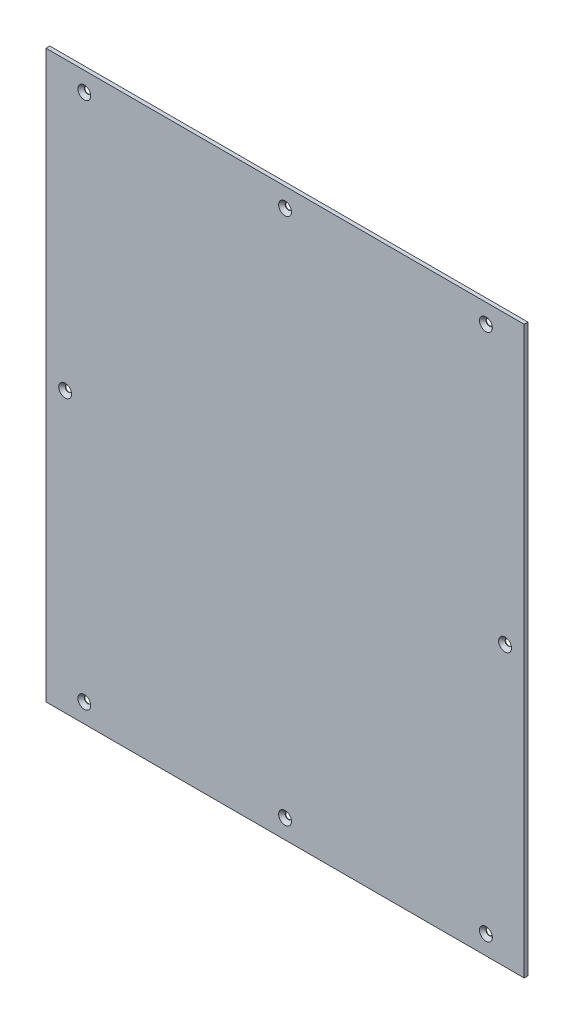
SolidWorks part; units mm, degrees
ref_plane "Front Plane" through (0, 0, 0) normal (0, 0, 1) x (1, 0, 0)
ref_plane "Top Plane" through (0, 0, 0) normal (0, 1, 0) x (1, 0, 0)
ref_plane "Right Plane" through (0, 0, 0) normal (1, 0, 0) x (0, 0, -1)
sketch "Sketch1" plane through (0, 0, 0) normal (0, 0, 1) x (1, 0, 0)
  line L1 (-250, -296) -> (250, -296)
  line L2 (-250, -296) -> (-250, 296)
  line L3 (-250, 296) -> (250, 296)
  line L4 (250, -296) -> (250, 296)
  line L5 (-250, -296) -> (250, 296) construction
  line L6 (-250, 296) -> (250, -296) construction
  point P0 (0, 0)
  dimension "D1" = 500
  dimension "D2" = 592
extrude "Boss-Extrude1" add sketch "Sketch1" along normal blind 4
sketch "Sketch2" plane through (0, 0, 4) normal (0, 0, 1) x (1, 0, 0)
  line L0 (-230, 378.3904) -> (-230, -313.5535) construction
  line L17 (-435.4748, 276) -> (450.358, 276) construction
  line L18 (-427.4037, -276) -> (432.8239, -276) construction
  line L19 (-250, 296) -> (-250, -296) construction
  line L20 (-250, -296) -> (250, -296) construction
  line L21 (250, 296) -> (-250, 296) construction
  line L22 (250, -296) -> (250, 296) construction
  line L23 (230, 365.8937) -> (230, -292.0763) construction
  point P32 (-210, -276)
  point P33 (210, -276)
  point P34 (-210, 276)
  point P35 (210, 276)
  point P36 (-230, -4)
  point P37 (230, -4)
  point P38 (0, 276)
  point P39 (0, -276)
  dimension "D2" = 40
  dimension "D3" = 40
  dimension "D4" = 40
  dimension "D5" = 40
  dimension "D6" = 300
  dimension "D7" = 20
  dimension "D8" = 300
  dimension "D9" = 20
  dimension "D10" = 20
  dimension "D11" = 20
  dimension "D18" = 0
  dimension "D19" = 0
hole_wizard "CSK for M6 Hex Socket Countersunk Cap Screw1" positions "Sketch3" profile "Sketch4" countersink size "M6" standard "ISO" end condition through all
sketch "Sketch3" plane through (0, 0, 4) normal (0, 0, 1) x (1, 0, 0)
  point P0 (-230, -4)
  point P3 (230, -4)
  point P6 (-210, -276)
  point P9 (0, -276)
  point P12 (210, -276)
  point P15 (210, 276)
  point P18 (0, 276)
  point P21 (-210, 276)
sketch "Sketch4" plane through (-230, -4, 4) normal (1, 0, 0) x (0, -1, 0)
  line L0 (0, 0) -> (0, 4)
  line L1 (0, 4) -> (3.3, 4)
  line L2 (3.3, 4) -> (3.3, 3.42)
  line L3 (3.3, 3.42) -> (6.72, 0)
  line L5 (6.72, 0) -> (0, 0)
  line L6 (-3.3, 3.42) -> (-6.72, 0) construction
  line L11 (0, -6.35) -> (0, 107.95) construction
  dimension "Thru Hole Dia." = 6.6
  dimension "Thru Hole Depth" = 4
  dimension "Near C'Sink Dia." = 13.44
  dimension "Near C'Sink Angle" = 90
